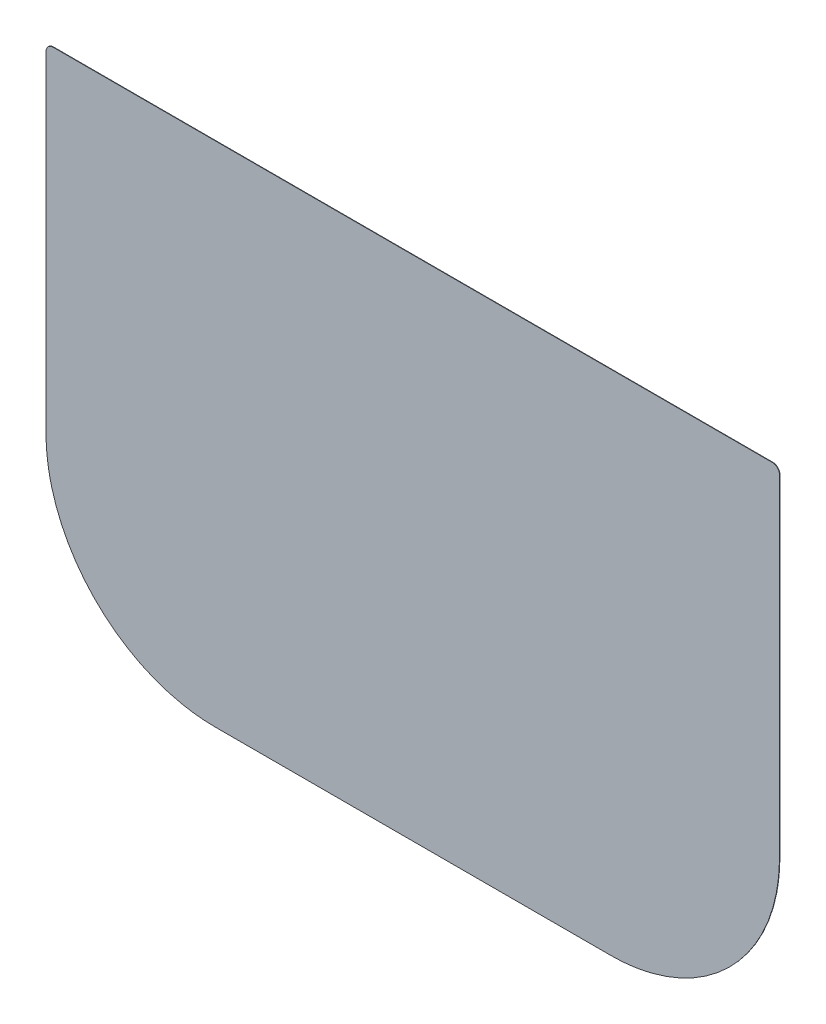
SolidWorks part; units mm, degrees
ref_plane "Front Plane" through (0, 0, 0) normal (0, 0, 1) x (1, 0, 0)
ref_plane "Top Plane" through (0, 0, 0) normal (0, 1, 0) x (1, 0, 0)
ref_plane "Right Plane" through (0, 0, 0) normal (1, 0, 0) x (0, 0, -1)
sketch "Model" plane through (0, 0, 0) normal (0, 0, 1) x (1, 0, 0)
  line L0 (311.4628, 29.1567) -> (133.8776, 29.1567)
  line L1 (57.5732, 105.4611) -> (57.5732, 254.5774)
  line L2 (60.7525, 257.7567) -> (384.594, 257.7567)
  line L3 (387.7732, 254.5774) -> (387.7732, 105.4671)
  arc A0 (118.9876, 30.6087) -> (133.8776, 29.1567) centre (133.8446, 105.8892) ccw
  arc A1 (94.6449, 40.0018) -> (118.9876, 30.6087) centre (133.6951, 104.9632) ccw
  arc A2 (67.4758, 67.8422) -> (94.6449, 40.0018) centre (134.1428, 105.7247) ccw
  arc A3 (60.0755, 86.007) -> (67.4758, 67.8422) centre (133.4736, 105.3193) ccw
  arc A4 (58.1977, 95.6534) -> (60.0755, 86.007) centre (133.6572, 105.3366) ccw
  arc A5 (57.5732, 105.4611) -> (58.1977, 95.6534) centre (134.9329, 105.4629) ccw
  arc A6 (60.7525, 257.7567) -> (57.5732, 254.5774) centre (60.7522, 254.5777) ccw
  arc A7 (387.7732, 254.5774) -> (384.594, 257.7567) centre (384.594, 254.5774) ccw
  arc A8 (386.3211, 90.5759) -> (387.7732, 105.4671) centre (311.0254, 105.435) ccw
  arc A9 (376.9272, 66.2311) -> (386.3211, 90.5759) centre (311.958, 105.2855) ccw
  arc A10 (349.0847, 39.06) -> (376.9272, 66.2311) centre (311.1979, 105.7335) ccw
  arc A11 (330.9185, 31.6591) -> (349.0847, 39.06) centre (311.6015, 105.0706) ccw
  arc A12 (321.2713, 29.7812) -> (330.9185, 31.6591) centre (311.5831, 105.2686) ccw
  arc A13 (311.4628, 29.1567) -> (321.2713, 29.7812) centre (311.4594, 106.5486) ccw
extrude "Boss-Extrude1" add sketch "Model" along normal blind 0.2
pattern_linear "LPattern1" [suppressed] count 2 spacing 350 count 2 spacing 250
move or copy body "Body-Move/Copy1" [suppressed] bodies to move or copy 101 102 copy no rotation origin (397.6732, 143.4567, 0) rotation axis (0, 0, 1) rotation angle 180
